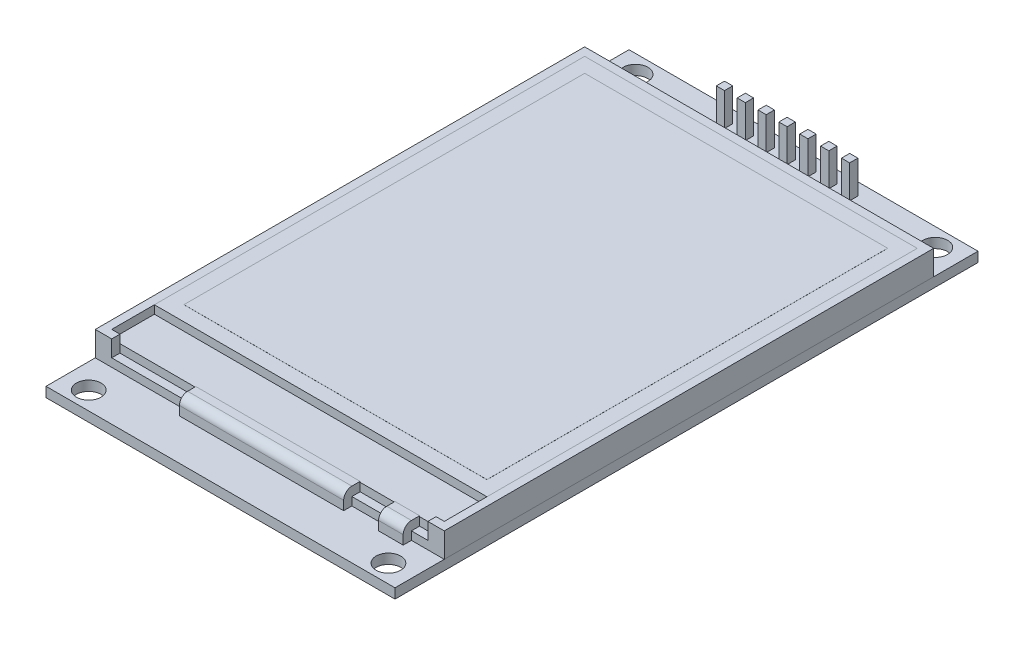
SolidWorks part; units mm, degrees
material "ABS"
ref_plane "Front Plane" through (0, 0, 0) normal (0, 0, 1) x (1, 0, 0)
ref_plane "Top Plane" through (0, 0, 0) normal (0, 1, 0) x (1, 0, 0)
ref_plane "Right Plane" through (0, 0, 0) normal (1, 0, 0) x (0, 0, -1)
sketch "Sketch1" plane through (0, 0, 0) normal (0, 1, 0) x (1, 0, 0)
  line L1 (-21.25, 35.5) -> (21.25, 35.5)
  line L2 (-21.25, 35.5) -> (-21.25, -35.5)
  line L3 (-21.25, -35.5) -> (21.25, -35.5)
  line L4 (21.25, 35.5) -> (21.25, -35.5)
  line L5 (0, -35.5) -> (0, 35.5) construction
  line L6 (-21.25, 0) -> (21.25, 0) construction
  point P0 (0, 0)
  dimension "D1" = 42.5
  dimension "D2" = 71
extrude "Boss-Extrude1" add sketch "Sketch1" along normal blind 1.2
sketch "Sketch7" plane through (0, 1.2, 0) normal (0, 1, 0) x (1, 0, 0)
  line L0 (-21.25, 35.5) -> (21.25, 35.5) construction
  line L1 (-21.25, 35.5) -> (-21.25, -35.5) construction
  circle A0 centre (-18.25, 33.3) radius 1.5
  dimension "D1" = 3
  dimension "D2" = 2.2
  dimension "D3" = 3
extrude "Cut-Extrude2" cut sketch "Sketch7" against normal through all
mirror "Mirror1" about plane through (0, 0, 0) normal (0, 0, 1) of "Cut-Extrude2" second plane through (0, 0, 0) second plane normal (1, 0, 0)
sketch "Sketch8" plane through (0, 1.2, 0) normal (0, 1, 0) x (1, 0, 0)
  line L0 (0, -10.821) -> (0, 10.821) construction
  line L1 (-0.5, 34) -> (0.5, 34)
  line L2 (-0.5, 34) -> (-0.5, 33)
  line L3 (-0.5, 33) -> (0.5, 33)
  line L4 (0.5, 34) -> (0.5, 33)
  line L5 (0, 33) -> (0, 34) construction
  line L6 (-0.5, 33.5) -> (0.5, 33.5) construction
  line L7 (-21.25, 35.5) -> (21.25, 35.5) construction
  point P0 (0, 33.5)
  dimension "D1" = 2
  dimension "D2" = 1
extrude "Boss-Extrude5" add sketch "Sketch8" along normal blind 4 and the other way blind 8
pattern_linear "LPattern1" count 4 spacing 2.54 along (1, 0, 0) count 4 spacing 2.54 along (-1, 0, 0) of "Boss-Extrude5"
sketch "Sketch10" plane through (0, 0, 0) normal (0, -1, 0) x (1, 0, 0)
  line L0 (-21.25, -35.5) -> (-21.25, 35.5) construction
  line L1 (-12.75, -24.5) -> (-3.85, -24.5)
  line L2 (-12.75, -24.5) -> (-12.75, -6.5)
  line L3 (-12.75, -6.5) -> (-3.85, -6.5)
  line L4 (-3.85, -24.5) -> (-3.85, -6.5)
  line L5 (-21.25, -35.5) -> (21.25, -35.5) construction
  dimension "D1" = 8.5
  dimension "D2" = 11
  dimension "D3" = 18
  dimension "D4" = 8.9
extrude "PCB components" add sketch "Sketch10" along normal blind 1.8 separate body
sketch "Sketch2" plane through (0, 1.2, 0) normal (0, 1, 0) x (1, 0, 0)
  line L1 (-21.25, 30.1) -> (21.25, 30.1)
  line L2 (-21.25, 30.1) -> (-21.25, -29.5)
  line L3 (-21.25, -29.5) -> (21.25, -29.5)
  line L4 (21.25, 30.1) -> (21.25, -29.5)
  line L6 (-21.25, 35.5) -> (-21.25, -35.5) construction
  line L7 (21.25, 35.5) -> (21.25, -35.5) construction
  line L8 (-21.25, 35.5) -> (21.25, 35.5) construction
  line L9 (-21.25, -35.5) -> (21.25, -35.5) construction
  line L10 (-21.25, 0.3) -> (21.25, 0.3) construction
  point P4 (0, 0.3)
  dimension "D1" = 5.4
  dimension "D2" = 6
extrude "Boss-Extrude2" add sketch "Sketch2" along normal blind 3 separate body
sketch "Sketch3" plane through (0, 4.2, 0) normal (0, 1, 0) x (1, 0, 0)
  line L1 (-20.25, 29.1) -> (20.25, 29.1)
  line L2 (-20.25, 29.1) -> (-20.25, -28.5)
  line L3 (-20.25, -28.5) -> (20.25, -28.5)
  line L4 (20.25, 29.1) -> (20.25, -28.5)
  line L5 (0, -10.821) -> (0, 10.821) construction
  line L6 (-21.25, 30.1) -> (21.25, 30.1) construction
  line L7 (-21.25, 35.5) -> (-21.25, -35.5) construction
  line L9 (-21.25, 0.3) -> (21.25, 0.3) construction
  point P8 (0, 29.1)
  point P12 (-20.25, 0.3)
  dimension "D1" = 1
  dimension "D2" = 1
extrude "Cut-Extrude1" cut sketch "Sketch3" against normal through all
sketch "Sketch12" plane through (0, 0, 29.5) normal (0, 0, 1) x (1, 0, 0)
  line L0 (0, -10.821) -> (0, 10.821) construction
  line L1 (-19.25, 4.2) -> (19.25, 4.2)
  line L2 (-19.25, 4.2) -> (-19.25, 2.2)
  line L3 (-19.25, 2.2) -> (19.25, 2.2)
  line L4 (19.25, 4.2) -> (19.25, 2.2)
  line L5 (-21.25, 4.2) -> (21.25, 4.2) construction
  line L6 (-21.25, 1.2) -> (21.25, 1.2) construction
  point P4 (0, 4.2)
  point P9 (13.6891, 2.4375)
  dimension "D1" = 2
  dimension "D2" = 1
extrude "Cut-Extrude4" cut sketch "Sketch12" against normal up to surface (1 mm away) up to face at (0, 2.7, 28.5)
sketch "Sketch5" plane through (0, 1.2, 0) normal (0, 1, 0) x (1, 0, 0)
  line L4 (20.25, 29.1) -> (-20.25, 29.1)
  line L5 (20.25, -28.5) -> (20.25, 29.1)
  line L6 (-20.25, -28.5) -> (20.25, -28.5)
  line L7 (-20.25, 29.1) -> (-20.25, -28.5)
  line L8 (20.25, 29.1) -> (-20.25, 29.1)
  line L9 (20.25, -28.5) -> (20.25, 29.1)
  line L10 (-20.25, -28.5) -> (20.25, -28.5)
  line L11 (-20.25, 29.1) -> (-20.25, -28.5)
  dimension "D1" = 0
extrude "Boss-Extrude3" add sketch "Sketch5" along normal up to surface (3 mm away) separate body up to face at (0, 4.2, 9.4667)
sketch "Sketch9" plane through (0, 4.2, 0) normal (0, 1, 0) x (1, 0, 0)
  line L0 (20.25, 29.1) -> (20.25, -28.5) construction
  line L1 (-20.25, -28.5) -> (20.25, -28.5)
  line L2 (-20.25, -28.5) -> (-20.25, -23.3)
  line L3 (-20.25, -23.3) -> (20.25, -23.3)
  line L4 (20.25, -28.5) -> (20.25, -23.3)
  line L5 (-21.25, -29.5) -> (21.25, -29.5) construction
  dimension "D1" = 6.2
extrude "Cut-Extrude3" cut sketch "Sketch9" against normal blind 1
sketch "Sketch6" plane through (0, 4.2, 0) normal (0, 1, 0) x (1, 0, 0)
  line L0 (0, -10.821) -> (0, 10.821) construction
  line L1 (-18.45, 27.3) -> (18.45, 27.3)
  line L2 (-18.45, 27.3) -> (-18.45, -21.5)
  line L3 (-18.45, -21.5) -> (18.45, -21.5)
  line L4 (18.45, 27.3) -> (18.45, -21.5)
  line L5 (21.25, 35.5) -> (-21.25, 35.5) construction
  line L6 (-20.25, 29.1) -> (20.25, 29.1) construction
  line L7 (-20.25, 29.1) -> (-20.25, -28.5) construction
  line L12 (20.25, 29.1) -> (-20.25, 29.1) construction
  line L13 (-20.25, 29.1) -> (-20.25, -28.5) construction
  line L14 (-21.25, 35.5) -> (-21.25, -35.5) construction
  line L15 (-20.25, -23.3) -> (20.25, -23.3) construction
  line L16 (20.25, -23.3) -> (-20.25, -23.3) construction
  line L17 (-21.25, -35.5) -> (21.25, -35.5) construction
  point P4 (0, 27.3)
  dimension "D1" = 1.8
  dimension "D2" = 1.8
  dimension "D3" = 1.8
  dimension "D4" = 12.2
  dimension "D7" = 6.4
  dimension "D8" = 1
extrude "Boss-Extrude4" add sketch "Sketch6" along normal blind 0.01
sketch "Sketch11" plane through (0, 1.2, 0) normal (0, 1, 0) x (1, 0, 0)
  line L0 (0, -10.821) -> (0, 10.821) construction
  line L1 (-10, -30.5) -> (10, -30.5)
  line L2 (-10, -30.5) -> (-10, -28.5)
  line L3 (-10, -28.5) -> (10, -28.5)
  line L4 (10, -30.5) -> (10, -28.5)
  line L5 (-20.25, -28.5) -> (20.25, -28.5) construction
  line L6 (-21.25, -29.5) -> (21.25, -29.5) construction
  line L7 (21.25, 35.5) -> (21.25, -35.5) construction
  line L8 (14.25, -28.5) -> (17.25, -28.5)
  line L9 (14.25, -28.5) -> (14.25, -30.5)
  line L10 (14.25, -30.5) -> (17.25, -30.5)
  line L11 (17.25, -28.5) -> (17.25, -30.5)
  point P4 (0, -28.5)
  dimension "D1" = 1
  dimension "D2" = 20
  dimension "D3" = 3
  dimension "D4" = 4
extrude "Boss-Extrude7" add sketch "Sketch11" along normal offset from surface (2.1 mm away) 0.1 separate body up to face at (0, 3.2, 25.9) offset beyond the face yes
fillet "Fillet1" radius 1 1 edges at (0, 3.3, 30.5)
fillet "Fillet2" radius 1 1 edges at (15.75, 3.3, 30.5)
